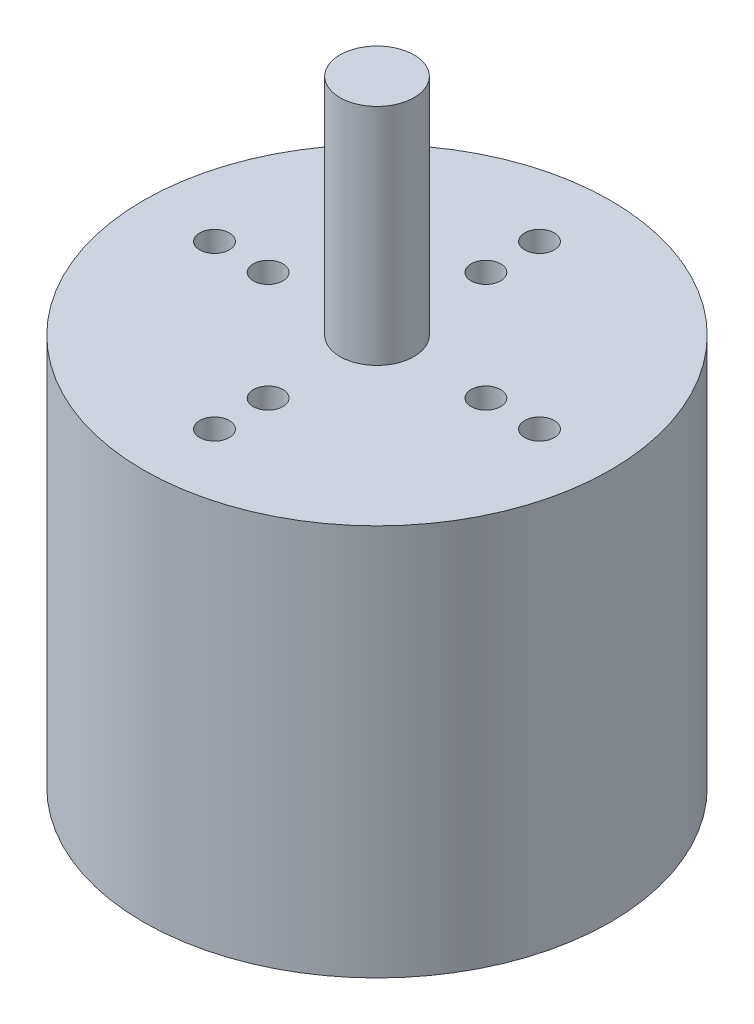
SolidWorks part; units mm, degrees
ref_plane "Front Plane" through (0, 0, 0) normal (0, 0, 1) x (1, 0, 0)
ref_plane "Top Plane" through (0, 0, 0) normal (0, 1, 0) x (1, 0, 0)
ref_plane "Right Plane" through (0, 0, 0) normal (1, 0, 0) x (0, 0, -1)
sketch "Sketch1" plane through (0, 0, 0) normal (0, 1, 0) x (1, 0, 0)
  circle A0 centre (0, 0) radius 31.525
  dimension "D1" = 63.05
extrude "Boss-Extrude1" add sketch "Sketch1" along normal blind 52.86
sketch "Sketch2" plane through (0, 52.86, 0) normal (0, 1, 0) x (1, 0, 0)
  circle A0 centre (0, 0) radius 5
  dimension "D1" = 10
extrude "Boss-Extrude2" add sketch "Sketch2" along normal blind 30.28
sketch "Sketch3" plane through (0, 52.86, 0) normal (0, 1, 0) x (1, 0, 0)
  circle A0 centre (0, 14.7) radius 2
  circle A1 centre (0, 21.94) radius 2
  circle A3 centre (0, 0) radius 5 construction
  circle A4 centre (0, 0) radius 5 construction
  dimension "D1" = 4
  dimension "D2" = 4
  dimension "D3" = 19.7
  dimension "D4" = 26.94
extrude "Cut-Extrude1" cut sketch "Sketch3" against normal blind 3
pattern_circular "CirPattern11" count 4 over 360 about axis through (0, 0, 0) along (0, 1, 0) of "Cut-Extrude1"
